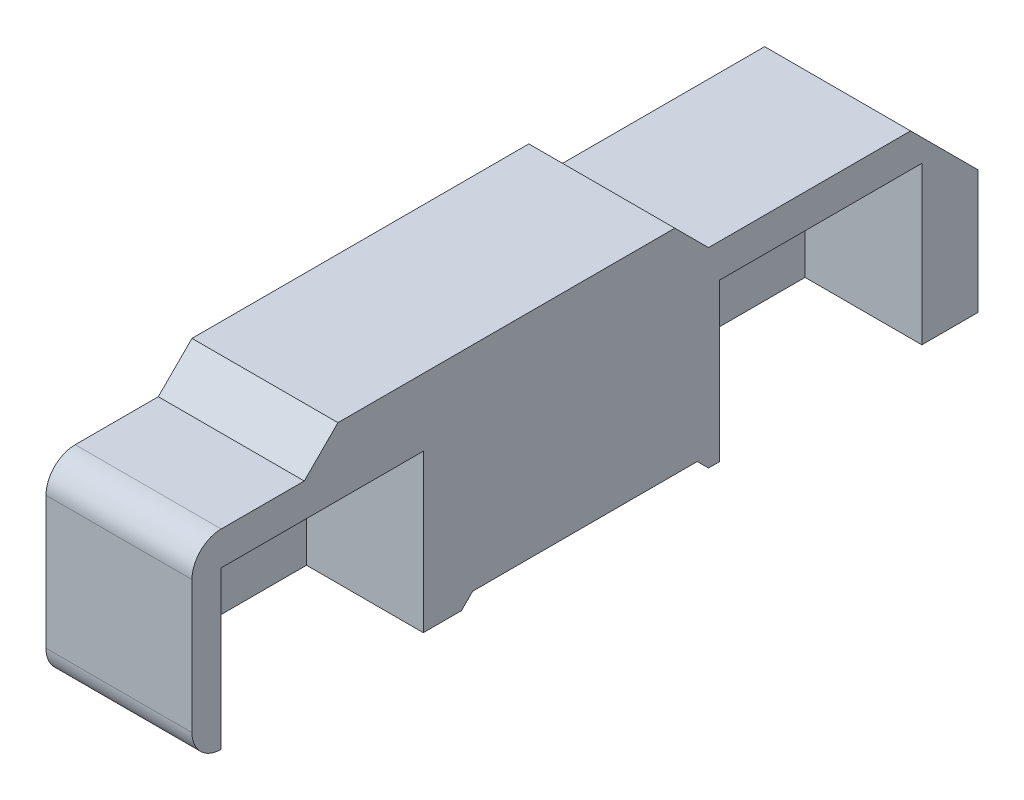
SolidWorks part; units mm, degrees
ref_plane "Front Plane" through (0, 0, 0) normal (0, 0, 1) x (1, 0, 0)
ref_plane "Top Plane" through (0, 0, 0) normal (0, 1, 0) x (1, 0, 0)
ref_plane "Right Plane" through (0, 0, 0) normal (1, 0, 0) x (0, 0, -1)
sketch "Sketch1" plane through (0, 0, 0) normal (0, 1, 0) x (1, 0, 0)
  line L1 (0, 0) -> (150, 0)
  line L2 (0, 0) -> (0, 350)
  line L3 (0, 350) -> (150, 350)
  line L4 (150, 0) -> (150, 350)
  dimension "D1" = 150
  dimension "D2" = 350
sketch "Sketch2" plane through (0, 0, 0) normal (1, 0, 0) x (0, 0, -1)
  line L0 (0, 0) -> (350, 0) construction
  line L1 (0, 0) -> (0, 85)
  line L2 (0, 85) -> (50, 85)
  line L3 (50, 85) -> (65, 100)
  line L4 (65, 100) -> (215, 100)
  line L5 (215, 100) -> (230, 85)
  line L6 (230, 85) -> (320, 85)
  line L7 (320, 85) -> (350, 55)
  line L8 (350, 55) -> (350, 0)
  line L9 (0, 0) -> (120, 0)
  line L10 (120, 0) -> (125, 5)
  line L11 (125, 5) -> (225, 5)
  line L12 (225, 5) -> (230, 0)
  line L13 (230, 0) -> (350, 0)
  dimension "D1" = 350
  dimension "D2" = 85
  dimension "D3" = 50
  dimension "D4" = 15
  dimension "D5" = 150
  dimension "D6" = 90
  dimension "D7" = 135
  dimension "D8" = 120
  dimension "D9" = 5
  dimension "D10" = 45
extrude "Boss-Extrude1" add sketch "Sketch2" along normal blind 65
fillet "Fillet1" radius 13 2 edges at (32.5, 0, 0) (32.5, 85, 0)
sketch "Sketch3" plane through (65, 0, 0) normal (1, 0, 0) x (0, 0, -1)
  line L0 (230, 0) -> (350, 0) construction
  line L1 (13, 0) -> (103, 0)
  line L2 (13, 0) -> (13, 70)
  line L3 (13, 70) -> (103, 70)
  line L4 (103, 0) -> (103, 70)
  line L5 (235, 70) -> (325, 70)
  line L6 (235, 70) -> (235, 0)
  line L7 (235, 0) -> (325, 0)
  line L8 (325, 70) -> (325, 0)
  point P11 (0, 0)
  dimension "D1" = 90
  dimension "D2" = 70
  dimension "D3" = 90
  dimension "D4" = 70
  dimension "D5" = 5
extrude "Cut-Extrude1" cut sketch "Sketch3" against normal blind 52
